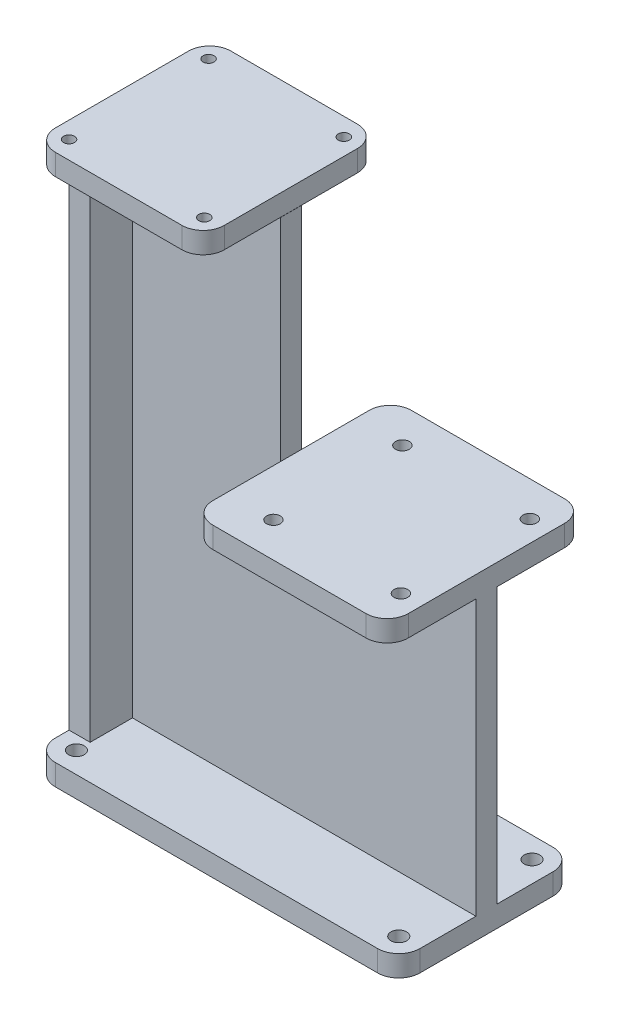
SolidWorks part; units mm, degrees
ref_plane "Front Plane" through (0, 0, 0) normal (0, 0, 1) x (1, 0, 0)
ref_plane "Top Plane" through (0, 0, 0) normal (0, 1, 0) x (1, 0, 0)
ref_plane "Right Plane" through (0, 0, 0) normal (1, 0, 0) x (0, 0, -1)
sketch "Skt - Base w mounting holes" plane through (0, 0, 0) normal (0, 1, 0) x (1, 0, 0)
  line L0 (-38.125, 20.75) -> (38.125, 20.75)
  line L1 (-38.125, -15.75) -> (38.125, -15.75) construction
  line L2 (-38.125, -15.75) -> (-38.125, 15.75) construction
  line L3 (-38.125, 15.75) -> (38.125, 15.75) construction
  line L4 (38.125, -15.75) -> (38.125, 15.75) construction
  line L5 (-38.125, -15.75) -> (38.125, 15.75) construction
  line L6 (-38.125, 15.75) -> (38.125, -15.75) construction
  line L7 (43.125, -15.75) -> (43.125, 15.75)
  line L8 (-38.125, -20.75) -> (38.125, -20.75)
  line L9 (-43.125, -15.75) -> (-43.125, 15.75)
  line L10 (-43.125, -20.75) -> (43.125, -20.75) construction
  line L11 (-43.125, -20.75) -> (-43.125, 20.75) construction
  line L12 (43.125, -20.75) -> (43.125, 20.75) construction
  line L13 (-43.125, 20.75) -> (43.125, 20.75) construction
  circle A0 centre (-38.125, 15.75) radius 1.85
  circle A1 centre (38.125, 15.75) radius 1.85
  circle A2 centre (38.125, -15.75) radius 1.85
  circle A3 centre (-38.125, -15.75) radius 1.85
  arc A4 (-38.125, -20.75) -> (-43.125, -15.75) centre (-38.125, -15.75) cw
  arc A5 (43.125, -15.75) -> (38.125, -20.75) centre (38.125, -15.75) cw
  arc A6 (38.125, 20.75) -> (43.125, 15.75) centre (38.125, 15.75) cw
  arc A7 (-38.125, 20.75) -> (-43.125, 15.75) centre (-38.125, 15.75) ccw
  point P0 (0, 0)
  dimension "D3" = 3.7
  dimension "D5" = 5
  dimension "D1" = 31.5
  dimension "D2" = 76.25
  dimension "D4" = 5
extrude "Ext - Base Plate w Mounting Holes" add sketch "Skt - Base w mounting holes" along normal blind 5 contours L8 A5 L7 A6 L0 A7 L9 A4
sketch "Skt - Upward Ridge" plane through (0, 5, 0) normal (0, 1, 0) x (1, 0, 0)
  line L0 (-43.125, 0) -> (43.125, 0) construction
  line L1 (-43.125, 15.75) -> (-43.125, -15.75) construction
  line L2 (43.125, -15.75) -> (43.125, 15.75) construction
  line L4 (-43.125, -2.5) -> (43.125, -2.5)
  line L5 (-43.125, -2.5) -> (-43.125, 2.5)
  line L6 (-43.125, 2.5) -> (43.125, 2.5)
  line L7 (43.125, -2.5) -> (43.125, 2.5)
  line L8 (-43.125, -2.5) -> (43.125, 2.5) construction
  line L9 (-43.125, 2.5) -> (43.125, -2.5) construction
  point P6 (0, 0)
  dimension "D1" = 5
extrude "Ext - Upward Flange" add sketch "Skt - Upward Ridge" along normal blind 65
sketch "Skt - GPS Nest" plane through (0, 70, 0) normal (0, 1, 0) x (1, 0, 0)
  line L0 (-43.125, 0) -> (43.125, 0) construction
  line L1 (-43.125, 2.5) -> (-43.125, -2.5) construction
  line L2 (43.125, -2.5) -> (43.125, 2.5) construction
  line L3 (43.125, -15.75) -> (43.125, -2.5) construction
  line L4 (1.875, 23.5) -> (38.125, 23.5)
  line L5 (-3.125, 18.5) -> (-3.125, -18.5)
  line L6 (1.875, -23.5) -> (38.125, -23.5)
  line L7 (43.125, 18.5) -> (43.125, -18.5)
  line L8 (-3.125, 23.5) -> (43.125, -23.5) construction
  line L9 (-3.125, -23.5) -> (43.125, 23.5) construction
  arc A0 (38.125, 23.5) -> (43.125, 18.5) centre (38.125, 18.5) cw
  arc A1 (-3.125, -18.5) -> (1.875, -23.5) centre (1.875, -18.5) ccw
  arc A2 (1.875, 23.5) -> (-3.125, 18.5) centre (1.875, 18.5) ccw
  arc A3 (38.125, -23.5) -> (43.125, -18.5) centre (38.125, -18.5) ccw
  point P6 (20, 0)
  dimension "D3" = 5
  dimension "D1" = 47
  dimension "D2" = 40
extrude "Ext - PIX Platform" add sketch "Skt - GPS Nest" along normal blind 5
sketch "Sketch7" plane through (0, 75, 0) normal (0, 1, 0) x (1, 0, 0)
  line L0 (-3.125, 0) -> (43.125, 0) construction
  line L1 (-3.125, 18.5) -> (-3.125, -18.5) construction
  line L2 (43.125, -18.5) -> (43.125, 18.5) construction
  line L3 (43.125, 0) -> (32.9734, 0) construction
  line L4 (7.975, -15.25) -> (38.125, -15.25) construction
  line L5 (7.975, -15.25) -> (7.975, 15.25) construction
  line L6 (38.125, -15.25) -> (38.125, 15.25) construction
  line L7 (7.975, 15.25) -> (38.125, 15.25) construction
  line L8 (7.975, -15.25) -> (38.125, 15.25) construction
  line L9 (38.125, -15.25) -> (7.975, 15.25) construction
  circle A0 centre (7.975, 15.25) radius 1.625
  circle A1 centre (38.125, 15.25) radius 1.625
  circle A2 centre (38.125, -15.25) radius 1.625
  circle A3 centre (7.975, -15.25) radius 1.625
  point P8 (23.05, 0)
  point P17 (43.125, 0)
  dimension "D4" = 3.25
  dimension "D1" = 30.5
  dimension "D2" = 5
  dimension "D3" = 30.15
extrude "Pix Mount Holes" cut sketch "Sketch7" against normal up to next
sketch "Sketch8" plane through (0, 70, 0) normal (0, 1, 0) x (1, 0, 0)
  line L1 (-43.125, 2.5) -> (-3.125, 2.5)
  line L2 (-43.125, 2.5) -> (-43.125, -2.5)
  line L3 (-43.125, -2.5) -> (-3.125, -2.5)
  line L4 (-3.125, 2.5) -> (-3.125, -2.5)
extrude "GPS Flange" add sketch "Sketch8" along normal blind 55
sketch "Sketch9" plane through (0, 125, 0) normal (0, 1, 0) x (1, 0, 0)
  line L0 (-43.125, 0) -> (-3.125, 0) construction
  line L1 (-43.125, 2.5) -> (-43.125, -2.5) construction
  line L2 (-3.125, -2.5) -> (-3.125, 2.5) construction
  line L3 (-38.125, -20.75) -> (38.125, -20.75) construction
  line L4 (-38.0944, 20.75) -> (-8.1556, 20.75)
  line L5 (-43.0944, 15.75) -> (-43.0944, -15.75)
  line L6 (-38.0944, -20.75) -> (-8.1556, -20.75)
  line L7 (-3.1556, 15.75) -> (-3.1556, -15.75)
  line L8 (-43.0944, 20.75) -> (-3.1556, -20.75) construction
  line L9 (-43.0944, -20.75) -> (-3.1556, 20.75) construction
  line L11 (-39.125, 16.5) -> (-7.125, 16.5) construction
  line L12 (-39.125, 16.5) -> (-39.125, -16.5) construction
  line L13 (-39.125, -16.5) -> (-7.125, -16.5) construction
  line L14 (-7.125, 16.5) -> (-7.125, -16.5) construction
  line L15 (-39.125, 16.5) -> (-7.125, -16.5) construction
  line L16 (-39.125, -16.5) -> (-7.125, 16.5) construction
  circle A0 centre (-39.125, 16.5) radius 1.3
  circle A1 centre (-7.125, 16.5) radius 1.3
  circle A2 centre (-7.125, -16.5) radius 1.3
  circle A3 centre (-39.125, -16.5) radius 1.3
  arc A4 (-43.0944, 15.75) -> (-38.0944, 20.75) centre (-38.0944, 15.75) cw
  arc A5 (-3.1556, -15.75) -> (-8.1556, -20.75) centre (-8.1556, -15.75) cw
  arc A6 (-3.1556, 15.75) -> (-8.1556, 20.75) centre (-8.1556, 15.75) ccw
  arc A7 (-43.0944, -15.75) -> (-38.0944, -20.75) centre (-38.0944, -15.75) ccw
  point P6 (-23.125, 0)
  point P13 (-23.125, 0)
  dimension "D3" = 2.6
  dimension "D4" = 5
  dimension "D1" = 32
  dimension "D2" = 33
extrude "GPS Platform" add sketch "Sketch9" along normal blind 5
sketch "Sketch10" plane through (-43.125, 0, 0) normal (-1, 0, 0) x (0, 0, 1)
  line L1 (-15.75, 125) -> (-2.5, 125) construction
  line L2 (-2.5, 5) -> (-12.5, 5)
  line L5 (0, 130) -> (0, 0) construction
  line L6 (-15.75, 130) -> (15.75, 130) construction
  line L15 (-2.5, 5) -> (-2.5, 125)
  line L20 (-2.5, 125) -> (-12.5, 125)
  line L21 (-12.5, 5) -> (-12.5, 125)
  line L22 (2.5, 125) -> (12.5, 125)
  line L23 (12.5, 5) -> (12.5, 125)
  line L24 (2.5, 5) -> (12.5, 5)
  line L25 (2.5, 5) -> (2.5, 125)
  dimension "D1" = 10
extrude "Bracing" add sketch "Sketch10" against normal blind 5
